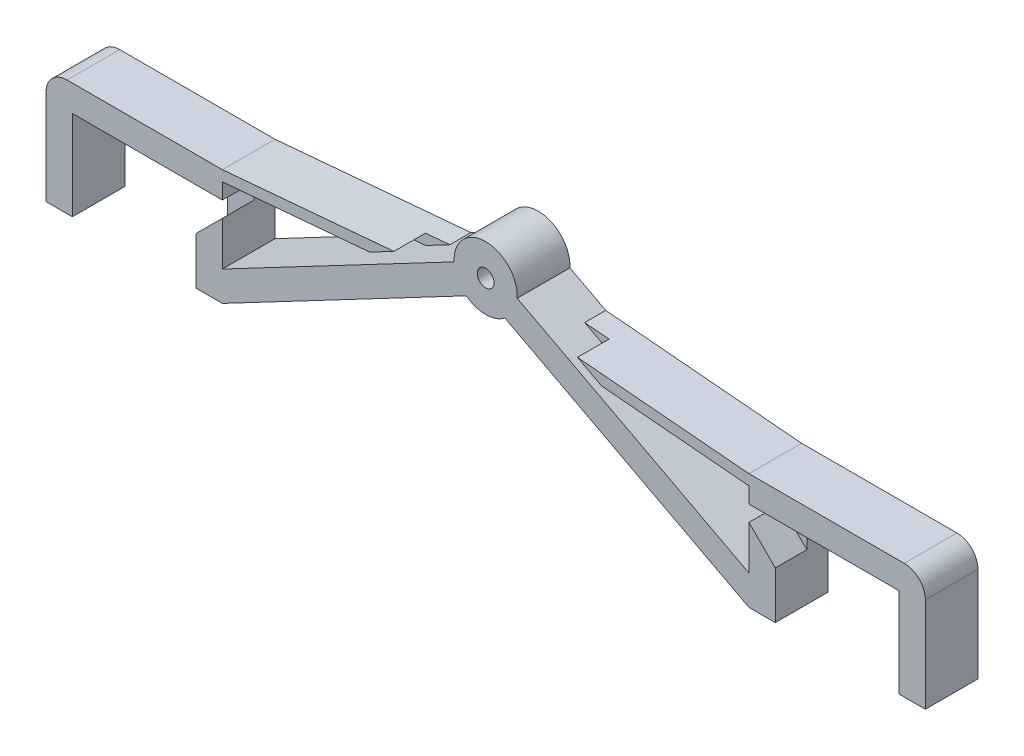
SolidWorks part; units mm, degrees
material "Plain Carbon Steel"
ref_plane "Front Plane" through (0, 0, 0) normal (0, 0, 1) x (1, 0, 0)
ref_plane "Top Plane" through (0, 0, 0) normal (0, 1, 0) x (1, 0, 0)
ref_plane "Right Plane" through (0, 0, 0) normal (1, 0, 0) x (0, 0, -1)
sketch "Sketch1" plane through (0, 0, 0) normal (0, 0, 1) x (1, 0, 0)
  line L0 (25, 85) -> (25, 0)
  line L1 (25, 0) -> (0, 0)
  line L2 (0, 0) -> (0, 110)
  line L3 (0, 110) -> (167.5, 110)
  line L4 (167.5, 110) -> (167.5, 28.2588)
  line L5 (167.5, 0) -> (142.5, 0)
  line L6 (142.5, 0) -> (142.5, 85)
  line L7 (142.5, 85) -> (25, 85)
  line L8 (25, 85) -> (25, 110) construction
  line L9 (167.5, 28.2588) -> (387.5457, 144.2151)
  line L10 (417.5, 160) -> (417.5, 131.7412) construction
  line L11 (399.2006, 122.0981) -> (167.5, 0)
  line L12 (142.5, 85) -> (167.5, 85) construction
  line L13 (387.5457, 144.2151) -> (417.5, 160) construction
  line L14 (417.5, 131.7412) -> (399.2006, 122.0981) construction
  line L15 (167.5, 14.1294) -> (417.5, 145.8706) construction
  line L16 (667.5, 14.1294) -> (417.5, 145.8706) construction
  line L17 (417.5, 131.7412) -> (435.7994, 122.0981) construction
  line L18 (447.4543, 144.2151) -> (417.5, 160) construction
  line L19 (692.5, 85) -> (667.5, 85) construction
  line L20 (810, 85) -> (810, 110) construction
  line L21 (435.7994, 122.0981) -> (667.5, 0)
  line L22 (667.5, 28.2588) -> (447.4543, 144.2151)
  line L23 (692.5, 85) -> (810, 85)
  line L24 (692.5, 0) -> (692.5, 85)
  line L25 (667.5, 0) -> (692.5, 0)
  line L26 (667.5, 110) -> (667.5, 28.2588)
  line L27 (835, 110) -> (667.5, 110)
  line L28 (835, 0) -> (835, 110)
  line L29 (810, 0) -> (835, 0)
  line L30 (810, 85) -> (810, 0)
  arc A0 (399.2006, 122.0981) -> (435.7994, 122.0981) centre (417.5, 145.8706) ccw
  arc A1 (447.4543, 144.2151) -> (387.5457, 144.2151) centre (417.5, 145.8706) ccw
  circle A2 centre (417.5, 145.8706) radius 8
  point P9 (417.5, 160)
  dimension "D7" = 60
  dimension "D8" = 16
  dimension "D1" = 25
  dimension "D2" = 85
  dimension "D3" = 117.5
  dimension "D4" = 275
  dimension "D5" = 50
  dimension "D6" = 25
extrude "Boss-Extrude1" add sketch "Sketch1" along normal mid plane 50
sketch "Sketch2" plane through (0, 85, 0) normal (0, -1, 0) x (1, 0, 0)
  line L0 (25, 0) -> (142.5, 0) construction
  line L1 (25, 25) -> (25, -25) construction
  line L2 (142.5, 25) -> (142.5, -25) construction
  line L3 (83.75, -25) -> (83.75, 25) construction
  line L4 (25, -25) -> (142.5, -25) construction
  line L5 (25, 25) -> (142.5, 25) construction
  line L6 (0, 0) -> (16.275, 0) construction
  line L7 (417.5, 25) -> (417.5, -25) construction
  line L8 (399.2006, -25) -> (435.7994, -25) construction
  line L9 (835, 0) -> (818.725, 0) construction
  line L10 (751.25, -25) -> (751.25, 25) construction
  line L11 (810, 0) -> (692.5, 0) construction
  circle A0 centre (16.275, 0) radius 5.25
  circle A1 centre (151.225, 0) radius 5.25
  circle A2 centre (683.775, 0) radius 5.25
  circle A3 centre (818.725, 0) radius 5.25
  dimension "D2" = 10.5
  dimension "D1" = 134.95
extrude "Cut-Extrude1" cut sketch "Sketch2" against normal blind 30 from surface at 85 starting at face at (12.5, 0, 0)
fillet "Fillet1" radius 20 2 edges at (835, 110, 0) (0, 110, 0)
sketch "Sketch3" plane through (0, 0, 25) normal (0, 0, 1) x (1, 0, 0)
  line L0 (167.5, 110) -> (353.4969, 126.2726)
  line L1 (387.5457, 144.2151) -> (167.5, 28.2588) construction
  line L2 (167.5, 110) -> (20, 110) construction
  line L3 (167.5, 99.9618) -> (330.6557, 114.2361)
  line L4 (167.5, 28.2588) -> (167.5, 110) construction
  line L5 (167.5, 110) -> (167.5, 99.9618)
  line L6 (353.4969, 126.2726) -> (330.6557, 114.2361)
  line L7 (417.5, 337.315) -> (417.5, -35.2717) construction
  line L8 (481.5031, 126.2726) -> (504.3443, 114.2361)
  line L9 (667.5, 110) -> (667.5, 99.9618)
  line L10 (667.5, 99.9618) -> (504.3443, 114.2361)
  line L11 (667.5, 110) -> (481.5031, 126.2726)
  dimension "D1" = 175
  dimension "D2" = 10
extrude "Boss-Extrude2" add sketch "Sketch3" against normal up to surface (50 mm away) contours L0 L6 L3 L5
sketch "Sketch4" plane through (0, 0, 25) normal (0, 0, 1) x (1, 0, 0)
  line L0 (142.5, 85) -> (167.5, 85)
  line L1 (167.5, 28.2588) -> (167.5, 99.9618) construction
  line L2 (167.5, 85) -> (167.5, 70)
  line L3 (167.5, 70) -> (142.5, 45)
  line L4 (142.5, 85) -> (142.5, 0) construction
  line L5 (142.5, 45) -> (142.5, 85)
  line L6 (330.6557, 114.2361) -> (353.4969, 126.2726)
  line L7 (353.4969, 126.2726) -> (330.3486, 124.2474)
  line L8 (353.4969, 126.2726) -> (167.5, 110) construction
  line L9 (330.3486, 124.2474) -> (307.5073, 112.2109)
  line L10 (167.5, 99.9618) -> (330.6557, 114.2361) construction
  line L11 (307.5073, 112.2109) -> (330.6557, 114.2361)
  line L12 (417.5, 304.2287) -> (417.5, -69.0223) construction
  line L13 (527.4927, 112.2109) -> (504.3443, 114.2361)
  line L14 (504.6514, 124.2474) -> (527.4927, 112.2109)
  line L15 (481.5031, 126.2726) -> (504.6514, 124.2474)
  line L16 (504.3443, 114.2361) -> (481.5031, 126.2726)
  line L17 (692.5, 45) -> (692.5, 85)
  line L18 (667.5, 70) -> (692.5, 45)
  line L19 (667.5, 85) -> (667.5, 70)
  line L20 (692.5, 85) -> (667.5, 85)
  dimension "D1" = 45
  dimension "D2" = 15
  dimension "D3" = 9
extrude "Cut-Extrude2" cut sketch "Sketch4" against normal blind 30
sketch "Sketch5" plane through (0, 0, -25) normal (0, 0, -1) x (-1, 0, 0)
  circle A0 centre (-417.5, 145.8706) radius 20.5
  dimension "D1" = 41
extrude "Cut-Extrude3" cut sketch "Sketch5" against normal blind 5
